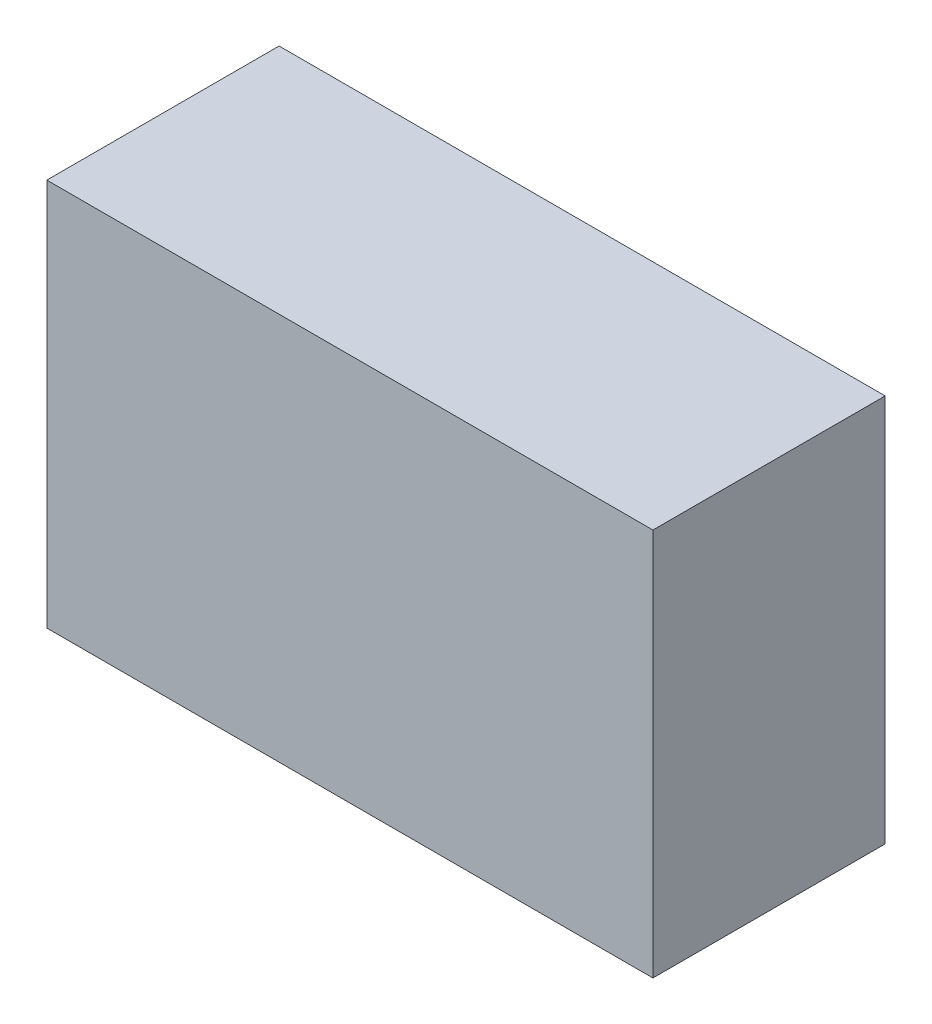
SolidWorks part; units mm, degrees
ref_plane "Front Plane" through (0, 0, 0) normal (0, 0, 1) x (1, 0, 0)
ref_plane "Top Plane" through (0, 0, 0) normal (0, 1, 0) x (1, 0, 0)
ref_plane "Right Plane" through (0, 0, 0) normal (1, 0, 0) x (0, 0, -1)
sketch "Sketch2" plane through (0, 0, 0) normal (0, 0, 1) x (1, 0, 0)
  line L1 (-69.1482, -44.2629) -> (69.1482, -44.2629)
  line L2 (-69.1482, -44.2629) -> (-69.1482, 44.2629)
  line L3 (-69.1482, 44.2629) -> (69.1482, 44.2629)
  line L4 (69.1482, -44.2629) -> (69.1482, 44.2629)
  line L5 (-69.1482, -44.2629) -> (69.1482, 44.2629) construction
  line L6 (-69.1482, 44.2629) -> (69.1482, -44.2629) construction
  point P0 (0, 0)
extrude "Boss-Extrude1" add sketch "Sketch2" along normal blind 53
